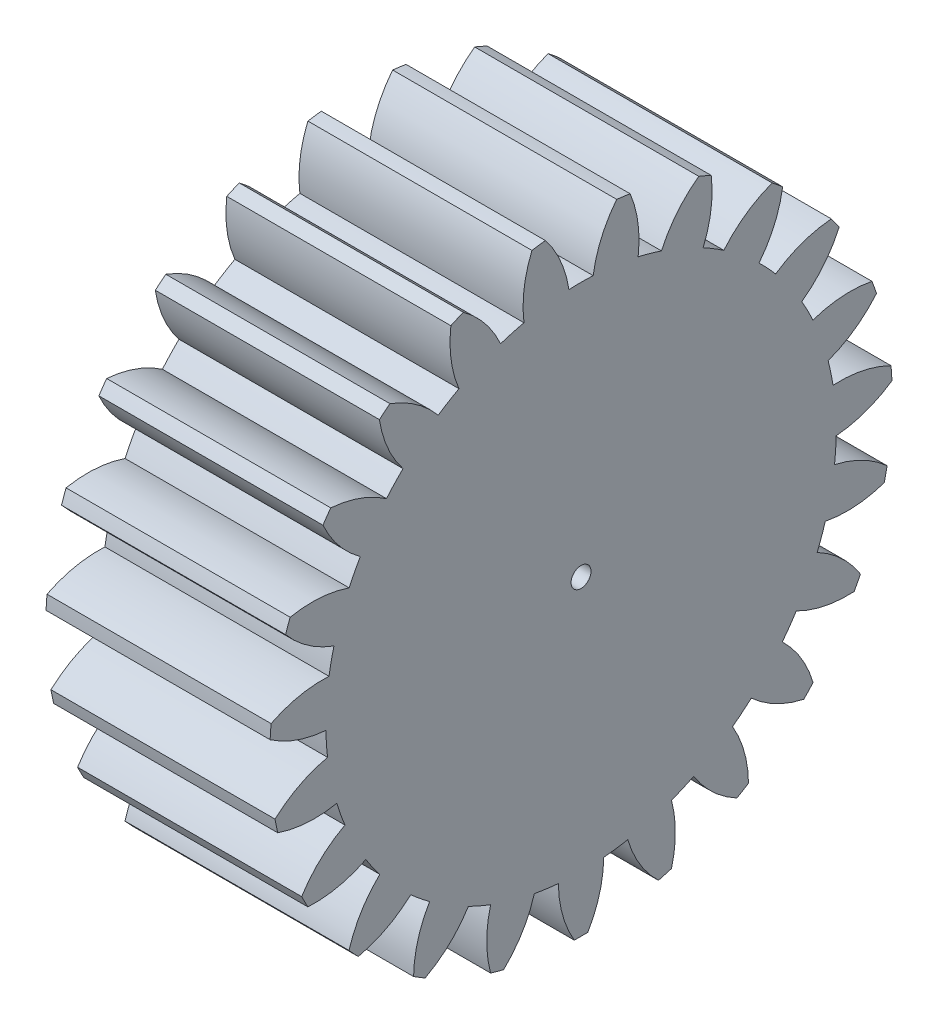
SolidWorks part; units mm, degrees
ref_plane "Plane1" through (0, 0, 0) normal (0, 0, 1) x (1, 0, 0)
ref_plane "Plane2" through (0, 0, 0) normal (0, 1, 0) x (1, 0, 0)
ref_plane "Plane3" through (0, 0, 0) normal (1, 0, 0) x (0, 0, -1)
other "Configuration Table"
sketch "HoldingSke" plane through (0, 0, 0) normal (0, 1, 0) x (1, 0, 0)
  line L0 (0, 0) -> (0.9205, -0.3907)
  line L1 (-15, 0) -> (100, 0) construction
  line L2 (0, 0) -> (-2.1039, 2.3779)
  line L3 (0, 0) -> (-11.863, 4.5341)
  line L4 (0, 0) -> (7.9495, 3.3744)
  line L5 (0, 0) -> (-46.8476, -17.4728)
  line L6 (0, 0) -> (-7.4607, -5.0337)
  line L7 (-2.1039, 2.3779) -> (8.6586, 51.2059)
  line L8 (-76.2, 54.61) -> (-76.1, 54.61)
  line L9 (-71.009, 38.7566) -> (-53.1078, 45.2721)
  line L10 (-76.2, 71.12) -> (104.1128, 71.12)
  line L11 (0, 0) -> (-9, 0)
  line L12 (-76.2, 101.6) -> (-76.162, 101.6)
  line L13 (24.9733, 27.94) -> (52.9518, 28.4284)
  line L14 (24.9733, 27.94) -> (24.9743, 27.94)
  line L15 (24.9733, 27.94) -> (100.4006, 29.5858)
  line L16 (-63.627, -1) -> (-12.827, -1)
  circle A0 centre (0, 0) radius 0.4
  circle A1 centre (0, 0) radius 10.249
  circle A2 centre (0, 0) radius 37.5
  circle A3 centre (0, 0) radius 0.4
  dimension "MHD" = 20.498
  dimension "Hub_dia" = 75
  dimension "Bore" = 0.8
  dimension "MBD" = 0.8
  dimension "Num_teeth" = 23
  dimension "Pitch" = 1
  dimension "Overall_len" = 50
  dimension "Show_teeth" = 23
  dimension "Thickness" = 9
  dimension "OAL" = 50.0001
  dimension "T_dim" = 0.1
  dimension "Ap" = 20
  dimension "H" = 19.05
  dimension "Pitch_radius" = 180.3128
  dimension "Width" = 9
  dimension "Backlash" = 0.038
  dimension "Addendum_fac" = 1
  dimension "Dedendum_fac" = 1.25
  dimension "Clearance_fac" = 0.25
  dimension "Dedendum_add" = 0.001
  dimension "Module" = 1
sketch "BasProSke" plane through (0, 0, 0) normal (0, 1, 0) x (1, 0, 0)
  line L0 (-10, 0) -> (60, 0) construction
  line L1 (0, 0) -> (0, 12.5)
  line L2 (0, 0) -> (9, 0)
  line L3 (9, 0) -> (9, 12.5)
  line L4 (9, 12.5) -> (0, 12.5)
  dimension "Thickness" = 9
  dimension "Diameter" = 25
revolve "Base-Revolve" add sketch "BasProSke" angle 360 about L0
sketch "TooCutSke" plane through (0, 0, 0) normal (1, 0, 0) x (0, 0, -1)
  line L1 (0, 0) -> (0, 107) construction
  line L2 (0, 0) -> (-0.8513, 11.4685) construction
  line L3 (0, 0) -> (-3.1257, 22.7413) construction
  line L4 (-0.8513, 11.4685) -> (-1.5629, 11.3706) construction
  arc A0 (0.4871, 10.2374) -> (-0.4871, 10.2374) centre (0, 0) ccw
  arc A1 (1.4505, 12.4411) -> (-1.4505, 12.4411) centre (0, 0) ccw
  circle A2 centre (0, 0) radius 11.5 construction
  circle A3 centre (0, 0) radius 10.8065 construction
  arc A4 (-0.4871, 10.2374) -> (-1.4505, 12.4411) centre (-5.037, 9.5608) ccw
  arc A5 (1.4505, 12.4411) -> (0.4871, 10.2374) centre (5.037, 9.5608) ccw
  dimension "Root_dia" = 20.498
  dimension "Overcut_dia" = 25.0508
  dimension "Pitch_dia" = 23
  dimension "Base_dia" = 21.6129
  dimension "Flank_rad" = 4.6
  dimension "Half_ang" = 7.826
  dimension "Half_CT" = 0.7183
extrude "ToothCut" cut sketch "TooCutSke" along normal through all
fillet "Breaks" [suppressed] radius 0.02
fillet "RootFillets" [suppressed] radius 0.251
pattern_circular "TeethCuts" count 23 every 15.652 about axis through (-10, 0, 0) along (1, 0, 0) of "ToothCut", "RootFillets", "Breaks"
sketch "HubNeaOneSke" plane through (0, 0, 0) normal (-1, 0, 0) x (0, 0, 1)
  circle A0 centre (0, 0) radius 10.249
  dimension "Diameter" = 20.498
extrude "HubNearOne" [suppressed] add sketch "HubNeaOneSke" along normal blind 41.0001
sketch "HubNeaBotSke" plane through (0, 0, 0) normal (-1, 0, 0) x (0, 0, 1)
  circle A0 centre (0, 0) radius 10.249
  dimension "Diameter" = 20.498
extrude "HubNearBoth" [suppressed] add sketch "HubNeaBotSke" along normal blind 20.5
ref_plane "FarPln" through (9, 0, 0) normal (1, 0, 0) x (0, 0, -1)
sketch "HubFarSke" plane through (9, 0, 0) normal (1, 0, 0) x (0, 0, -1)
  circle A0 centre (0, 0) radius 10.249
  dimension "Diameter" = 20.498
extrude "HubFar" [suppressed] add sketch "HubFarSke" along normal blind 20.5
sketch "BorSke" plane through (0, 0, 0) normal (1, 0, 0) x (0, 0, -1)
  circle A0 centre (0, 0) radius 0.4
  dimension "Diameter" = 0.8
extrude "Bore" cut sketch "BorSke" along normal mid plane 100.0001
sketch "KeySke" plane through (0, 0, 0) normal (1, 0, 0) x (0, 0, -1)
  line L0 (-0.05, 0) -> (-0.05, 0.5)
  line L1 (-0.05, 0.5) -> (0.05, 0.5)
  line L2 (0.05, 0.5) -> (0.05, 0)
  line L3 (0, 0) -> (0, 34) construction
  line L4 (-0.05, 0) -> (0.05, 0)
  dimension "Offset" = 0.5
  dimension "Width" = 0.1
extrude "Keyway" [suppressed] cut sketch "KeySke" along normal mid plane 100.0001
pattern_circular "Keyway2" [suppressed] count 2 every 90 about axis through (-10, 0, 0) along (1, 0, 0)
equation "' \"Module@HoldingSke\" = 6.35"
equation "' \"Num_teeth@HoldingSke\" = 12"
equation "' \"Ap@HoldingSke\" =  20"
equation "' \"Ap@HoldingSke\" = 20"
equation "' \"Width@HoldingSke\" = 0.5 * 25.4"
equation "' \"Hub_dia@HoldingSke\"= 1 * 25.4"
equation "' \"Hub_dia@HoldingSke\" = 1 * 25.4"
equation "' \"Overall_len@HoldingSke\" = 1.0 * 25.4"
equation "' \"Bore@HoldingSke\" = 0.75 * 25.4"
equation "' \"T_dim@HoldingSke\" = 0.1 * 25.4"
equation "' \"Width@KeySke\" = 0.25 * 25.4"
equation "' \"Show_teeth@HoldingSke\" = 13"
equation "' \"Backlash@HoldingSke\" = 0.009 * 25.4"
equation "' \"Addendum_fac@HoldingSke\" = 1.0"
equation "' \"Dedendum_fac@HoldingSke\" = 1.25"
equation "' \"Dedendum_add@HoldingSke\" = 0.00005 * 25.4"
equation "' \"Clearance_fac@HoldingSke\" = 0.25"
equation "\"Pitch@HoldingSke\" = 1 / \"Module@HoldingSke\""
equation "\"Overcut_dia@TooCutSke\" = (\"Num_teeth@HoldingSke\" + 2 * \"Addendum_fac@HoldingSke\") / \"Pitch@HoldingSke\" + 0.002 * 25.4"
equation "\"Pitch_dia@TooCutSke\" = \"Num_teeth@HoldingSke\" / \"Pitch@HoldingSke\""
equation "\"Base_dia@TooCutSke\" = \"Num_teeth@HoldingSke\" / \"Pitch@HoldingSke\" * cos((\"Ap@HoldingSke\"  * 3.14159265 / 180))"
equation "\"Root_dia@TooCutSke\" = (\"Num_teeth@HoldingSke\" + 2) / \"Pitch@HoldingSke\" - 2 * (\"Addendum_fac@HoldingSke\" + \"Dedendum_fac@HoldingSke\") / \"Pitch@HoldingSke\" - \"Dedendum_add@HoldingSke\" * 2"
equation "\"Half_ang@TooCutSke\" = 180 / \"Num_teeth@HoldingSke\""
equation "\"Half_CT@TooCutSke\" = \"Num_teeth@HoldingSke\" / \"Pitch@HoldingSke\" * sin((3.14159265 / 2 / \"Num_teeth@HoldingSke\")) / 2 - 7 * \"Backlash@HoldingSke\" / 4"
equation "\"Flank_rad@TooCutSke\" = \"Num_teeth@HoldingSke\" / \"Pitch@HoldingSke\" / 5"
equation "\"Radius@RootFillets\" = \"Clearance_fac@HoldingSke\" / \"Pitch@HoldingSke\" + \"Dedendum_add@HoldingSke\""
equation "\"Break_rad@Breaks\" = 0.02 / \"Pitch@HoldingSke\""
equation "\"Thickness@HoldingSke\" = \"Width@HoldingSke\""
equation "\"OAL@HoldingSke\" = \"Thickness@HoldingSke\""
equation "\"MHD@HoldingSke\" = (\"Num_teeth@HoldingSke\" + 2) / \"Pitch@HoldingSke\" - 2 * (\"Addendum_fac@HoldingSke\" + \"Dedendum_fac@HoldingSke\")  / \"Pitch@HoldingSke\" - \"Dedendum_add@HoldingSke\" * 2"
equation "\"MBD@HoldingSke\" = (\"Num_teeth@HoldingSke\" + 2) / \"Pitch@HoldingSke\" - 2 * (\"Addendum_fac@HoldingSke\" + \"Dedendum_fac@HoldingSke\")  / \"Pitch@HoldingSke\" - \"Dedendum_add@HoldingSke\" * 2 - 0.002 * 25.4"
equation "\"MHD@HoldingSke\" = ((sgn( \"MHD@HoldingSke\" - \"Hub_dia@HoldingSke\" )-1)*( \"MHD@HoldingSke\" - \"Hub_dia@HoldingSke\" ))/-2+ \"Hub_dia@HoldingSke\""
equation "\"MBD@HoldingSke\" = ((sgn( \"MBD@HoldingSke\" - \"Bore@HoldingSke\" )-1)*( \"MBD@HoldingSke\" - \"Bore@HoldingSke\" ))/-2+ \"Bore@HoldingSke\""
equation "\"OAL@HoldingSke\" = ((sgn( \"OAL@HoldingSke\" - \"Overall_len@HoldingSke\" )+1)*( \"OAL@HoldingSke\" - \"Overall_len@HoldingSke\" ))/2 + \"Overall_len@HoldingSke\" + 0.000002 * 25.4"
equation "\"Num_teeth@TeethCuts\" = int( \"Show_teeth@HoldingSke\" ) + 1"
equation "\"Num_teeth@TeethCuts\" = ((sgn( \"Num_teeth@TeethCuts\" - \"Num_teeth@HoldingSke\" )-1)*( \"Num_teeth@TeethCuts\" - \"Num_teeth@HoldingSke\" ))/-2+ \"Num_teeth@HoldingSke\""
equation "\"Num_teeth@TeethCuts\" = ((sgn( \"Num_teeth@TeethCuts\" - 2.0)+1)*( \"Num_teeth@TeethCuts\" - 2.0))/2 +2.0"
equation "\"Angle@TeethCuts\" = 360.0 / \"Num_teeth@HoldingSke\""
equation "\"Diameter@BasProSke\" = (\"Num_teeth@HoldingSke\" + 2 * \"Addendum_fac@HoldingSke\") / \"Pitch@HoldingSke\""
equation "\"Thickness@BasProSke\"  = \"Thickness@HoldingSke\""
equation "' \"Fillet_rad@BasProSke\" =  \"Thickness@HoldingSke\" * 0.05"
equation "' \"Fillet_rad@BasProSke\" = \"Thickness@HoldingSke\" * 0.05"
equation "\"MHD@HoldingSke\" = ((sgn( \"MHD@HoldingSke\" - \"Root_dia@TooCutSke\" )-1)*( \"MHD@HoldingSke\" - \"Root_dia@TooCutSke\" ))/-2+ \"Root_dia@TooCutSke\""
equation "\"Diameter@HubNeaOneSke\" = \"MHD@HoldingSke\""
equation "\"Length@HubNearOne\" = \"OAL@HoldingSke\" - \"Thickness@BasProSke\""
equation "\"Diameter@HubNeaBotSke\" = \"MHD@HoldingSke\""
equation "\"Length@HubNearBoth\" = ( \"OAL@HoldingSke\" - \"Thickness@BasProSke\" ) / 2.0"
equation "\"Thickness@FarPln\" = \"Thickness@BasProSke\""
equation "\"Diameter@HubFarSke\" = \"MHD@HoldingSke\""
equation "\"Length@HubFar\" = ( \"OAL@HoldingSke\" - \"Thickness@BasProSke\" ) / 2.0"
equation "\"Diameter@BorSke\" = \"MBD@HoldingSke\""
equation "\"D1@Bore\" = \"OAL@HoldingSke\" * 2.0"
equation "\"D1@Keyway\" = \"OAL@HoldingSke\" * 2.0"
equation "\"Offset@KeySke\" = \"T_dim@HoldingSke\" + \"MBD@HoldingSke\" / 2.0"
